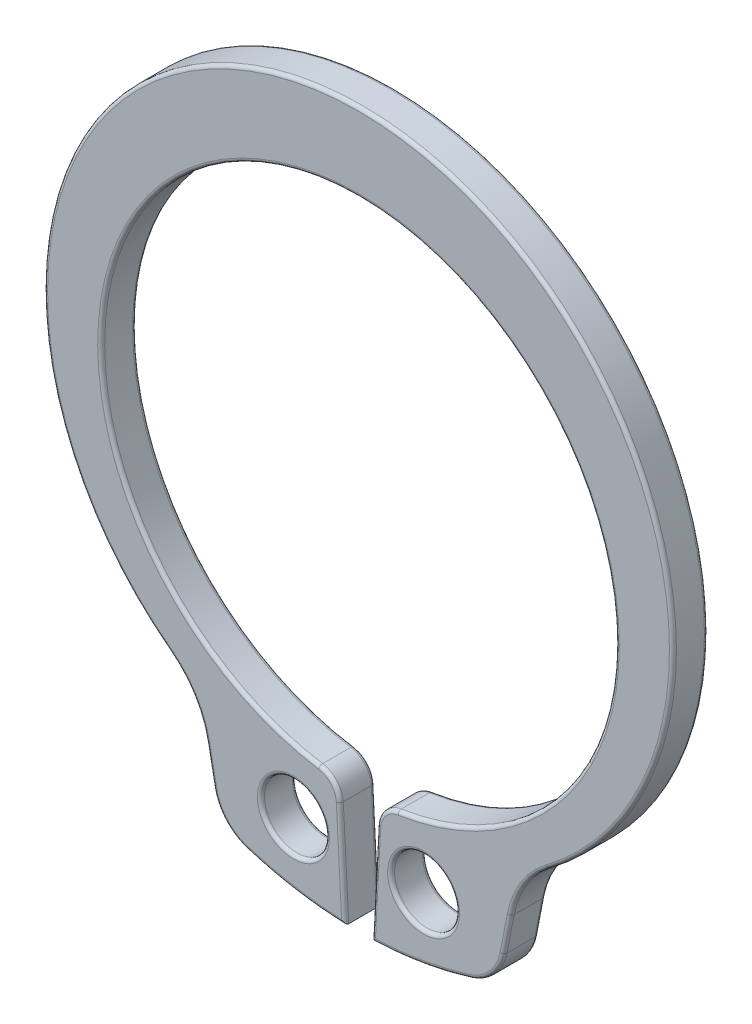
SolidWorks part; units mm, degrees
ref_plane "Front" through (0, 0, 0) normal (0, 0, 1) x (1, 0, 0)
ref_plane "Top" through (0, 0, 0) normal (0, 1, 0) x (1, 0, 0)
ref_plane "Right" through (0, 0, 0) normal (1, 0, 0) x (0, 0, -1)
sketch "Sketch1" plane through (0, 0, 0) normal (0, 0, 1) x (1, 0, 0)
  line L0 (0, 0) -> (-6.3653, -3.675) construction
  line L1 (0, 10.855) -> (0, -10.855) construction
  line L2 (-3.9914, -10.1017) -> (-4.5673, -7.1301) construction
  line L4 (-4.5673, -7.1301) -> (-5.1701, -8.0711) construction
  line L5 (-4.5673, -7.1301) -> (0, 0) construction
  line L6 (0, 7.35) -> (0, 9.585) construction
  line L7 (0, 9.585) -> (0, 8.4675) construction
  line L8 (0, -7.35) -> (0, -10.855) construction
  line L9 (-2.2174, -10.6329) -> (0, 0) construction
  line L10 (0, 0) -> (-0.3791, -10.855) construction
  line L11 (-3.9914, -10.1017) -> (0, 0) construction
  line L12 (-4.3762, -8.1161) -> (-5.4022, -6.5718) construction
  line L13 (-4.8892, -7.3439) -> (-4.5673, -7.1301) construction
  line L14 (-1.5005, -7.1952) -> (-2.2174, -10.6329) construction
  line L15 (-1.859, -8.914) -> (-0.9515, -9.1033) construction
  arc A0 (0, 9.585) -> (-4.5673, -7.1301) centre (0, 0.6035) ccw construction
  circle A2 centre (0, 0) radius 9.585 construction
  arc A3 (-3.9914, -10.1017) -> (-0.3791, -10.855) centre (0, 0) ccw construction
  circle A4 centre (0, 0) radius 7.35 construction
  circle A6 centre (-1.859, -8.914) radius 0.927 construction
  arc A7 (-5.4022, -6.5718) -> (-4.3762, -8.1161) centre (-7.0787, -8.7986) cw construction
  point P5 (-6.3653, -3.675)
  point P24 (-3.5222, -8.9144)
  point P35 (0, 9.585)
  point P36 (0, 7.35)
  point P37 (0, -7.35)
  point P38 (0, -10.855)
  dimension "Ring ID" = 14.7
  dimension "Hole Diameter" = 1.854
  dimension "D10" = 2.7874
  dimension "Max Sec." = 2.235
  dimension "Lug Height" = 3.505
  dimension "D6" = 2
  dimension "D5" = 3.0269
  dimension "D8" = 1.854
  dimension "D3" = 120
  dimension "D2" = 3.708
  dimension "D4" = 1.854
sketch "Sketch5" plane through (0, 0, 0) normal (0, 1, 0) x (1, 0, 0)
  line L0 (-9.585, 0.5) -> (-9.585, -0.5) construction
  line L2 (0, 0.5) -> (0, -0.5) construction
  line L4 (-9.585, 0) -> (9.585, 0) construction
  point P3 (-9.585, 0)
  point P6 (0, 0)
  dimension "Ring Thickness" = 1
sketch "Sketch2" plane through (0, 0, 0) normal (0, 0, 1) x (1, 0, 0)
  line L0 (-3.9914, -10.1017) -> (-4.5673, -7.1301) construction
  line L1 (-3.9914, -10.1017) -> (-4.5673, -7.1301)
  line L2 (0, 9.585) -> (0, 7.35)
  line L3 (0, 0) -> (-0.3791, -10.855) construction
  line L5 (-0.3791, -10.855) -> (-0.5639, -7.3283)
  arc A0 (0, 9.585) -> (-4.5673, -7.1301) centre (0, 0.6035) ccw construction
  arc A1 (-3.9914, -10.1017) -> (-0.3791, -10.855) centre (0, 0) ccw construction
  circle A2 centre (-1.859, -8.914) radius 0.927 construction
  arc A4 (0, 9.585) -> (-4.5673, -7.1301) centre (0, 0.6035) ccw
  arc A5 (-3.9914, -10.1017) -> (-0.3791, -10.855) centre (0, 0) ccw
  circle A6 centre (-1.859, -8.914) radius 0.927
  circle A7 centre (0, 0) radius 7.35 construction
  arc A8 (0, 7.35) -> (-0.5639, -7.3283) centre (0, 0) ccw
  dimension "D1" = 5
extrude "Boss-Extrude1" add sketch "Sketch2" along normal mid plane 1
fillet "Fillet1" radius 2.7874 1 edges at (-4.5673, -7.1301, 0)
fillet "Fillet2" radius 1.3937 1 edges at (-3.9914, -10.1017, 0)
fillet "Fillet3" radius 0.6968 1 edges at (-0.5639, -7.3283, 0)
mirror "Mirror1" about plane through (0, 9.585, 0.5) normal (-1, 0, 0) of bodies 109
sketch "Sketch3" plane through (0, 0, 0.5) normal (0, 0, 1) x (1, 0, 0)
  line L0 (4.7088, -5.6436) -> (5.4062, -6.5688) construction
  line L1 (5.4062, -6.5688) -> (6.3314, -5.8714) construction
  line L2 (0, 9.585) -> (0, 7.35) construction
  circle A0 centre (0, 0) radius 7.35 construction
  arc A1 (5.4062, -6.5688) -> (-5.4062, -6.5688) centre (0, 0.6035) ccw construction
fillet "Fillet4" radius 0.1 32 edges at (-0.4561, -9.3855, 0.5) (-0.932, -8.914, -0.5) (-0.932, -8.914, 0.5) (-4.2454, -8.7908, -0.5) (-4.2454, -8.7908, 0.5) (-4.7196, -7.3184, -0.5) (-4.7196, -7.3184, 0.5) (-1.7968, -10.712, -0.5) (-1.7968, -10.712, 0.5) (-3.8115, -9.984, -0.5) (-3.8115, -9.984, 0.5) (0, 7.35, -0.5) (0, 7.35, 0.5) (-0.712, -7.4852, -0.5) (-0.712, -7.4852, 0.5) (0, 9.585, 0.5) (0.932, -8.914, 0.5) (4.2454, -8.7908, -0.5) (1.7968, -10.712, -0.5) (0.4561, -9.3855, -0.5) (4.2454, -8.7908, 0.5) (1.7968, -10.712, 0.5) (0.4561, -9.3855, 0.5) (0.932, -8.914, -0.5) (4.7196, -7.3184, 0.5) (4.7196, -7.3184, -0.5) (3.8115, -9.984, 0.5) (3.8115, -9.984, -0.5) (0.712, -7.4852, 0.5) (0.712, -7.4852, -0.5) (-0.4561, -9.3855, -0.5) (0, 9.585, -0.5)
equation "\"D1@Fillet1\" = \"D10@Sketch1\""
equation "\"D1@Fillet2\"=\"D10@Sketch1\" / 2"
equation "\"Thickness@Boss-Extrude1\"=\"Ring Thickness@Sketch5\""
equation "\"D2@Sketch1\"=\"Hole Diameter@Sketch1\"*2"
equation "\"D4@Sketch1\"=\"D2@Sketch1\"/2"
equation "\"D8@Sketch1\"=\"D4@Sketch1\""
equation "\"D1@Fillet3\"=\"D1@Fillet2\"*.5"
equation "\"D1@Fillet4\"=\"Ring Thickness@Sketch5\"*.1"
